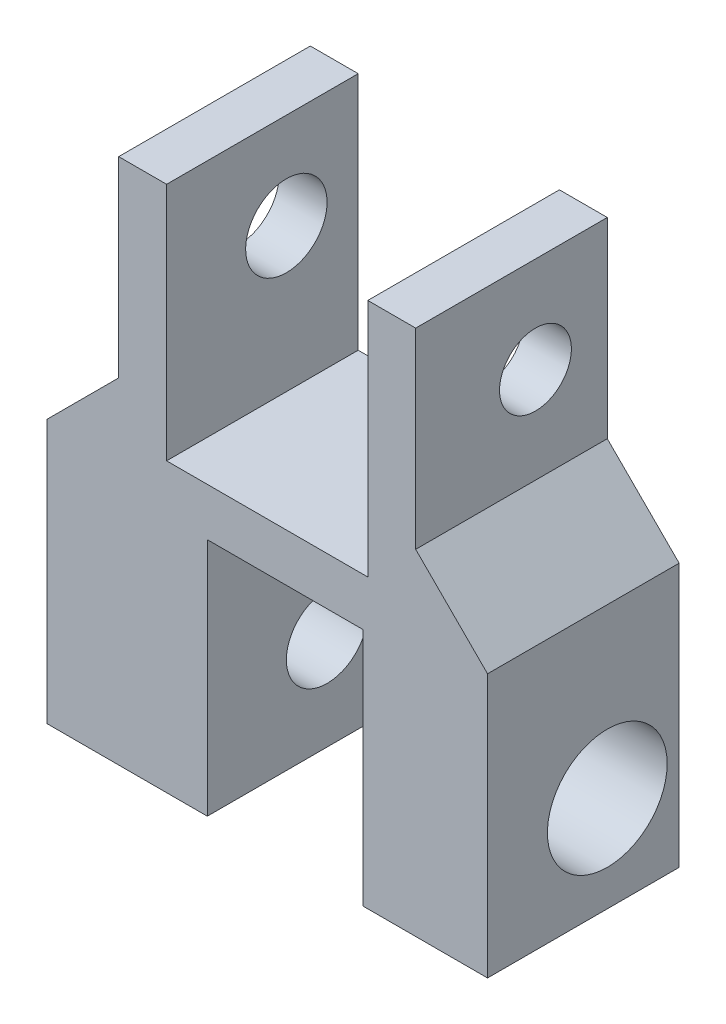
SolidWorks part; units mm, degrees
ref_plane "Ebene vorne" through (0, 0, 0) normal (0, 0, 1) x (1, 0, 0)
ref_plane "Ebene oben" through (0, 0, 0) normal (0, 1, 0) x (1, 0, 0)
ref_plane "Ebene rechts" through (0, 0, 0) normal (1, 0, 0) x (0, 0, -1)
sketch "Skizze2" plane through (0, 0, 0) normal (0, 0, 1) x (1, 0, 0)
  line L0 (-4.2, 0) -> (4.2, 0)
  line L1 (4.2, 0) -> (4.2, 10)
  line L2 (4.2, 10) -> (6.2, 10)
  line L3 (6.2, 10) -> (6.2, 2)
  line L4 (-6, -1) -> (-9.2, -1) construction
  line L5 (0, 0) -> (0, -14.4455) construction
  line L6 (-6.2, 10) -> (-6.2, 2)
  line L7 (-4.2, 10) -> (-6.2, 10)
  line L8 (-4.2, 0) -> (-4.2, 10)
  line L9 (-9.2, -1) -> (-9.2, -12)
  line L10 (-9.2, -12) -> (-2.5, -12)
  line L11 (9.2, -1) -> (9.2, -12)
  line L12 (6, -1) -> (9.2, -1) construction
  line L13 (-2.5, -12) -> (-2.5, -2)
  line L14 (-2.5, -2) -> (0, -2)
  line L15 (4, -12) -> (9.2, -12)
  line L16 (4, -12) -> (4, -2)
  line L17 (-9.2, -1) -> (-6.2, 2)
  line L18 (9.2, -1) -> (6.2, 2)
  line L19 (4, -2) -> (0, -2)
  dimension "D1" = 8.4
  dimension "D2" = 10
  dimension "D3" = 2
  dimension "D4" = 1
  dimension "D5" = 3
  dimension "D6" = 11
  dimension "D7" = 2.5
  dimension "D8" = 4
  dimension "D9" = 45
  dimension "D10" = 10
extrude "Aufsatz-Linear austragen1" add sketch "Skizze2" along normal blind 8
sketch "Skizze3" plane through (9.2, 0, 0) normal (-1, 0, 0) x (0, 0, 1)
  line L0 (4, -12) -> (4, -1) construction
  line L1 (8, -12) -> (0, -12) construction
  line L2 (8, -1) -> (0, -1) construction
  line L3 (0, -12) -> (0, -1) construction
  circle A0 centre (3, -8) radius 2.5
  dimension "D1" = 5
  dimension "D2" = 4
  dimension "D3" = 3
extrude "Schnitt-Linear austragen1" cut sketch "Skizze3" along normal blind 10
sketch "Skizze4" plane through (-9.2, 0, 0) normal (-1, 0, 0) x (0, 0, 1)
  circle A0 centre (3, -8) radius 1.7
  dimension "D1" = 3.4
extrude "Schnitt-Linear austragen2" cut sketch "Skizze4" against normal up to next
sketch "Skizze5" plane through (-6.2, 0, 0) normal (-1, 0, 0) x (0, 0, 1)
  line L0 (4, 10) -> (4, 2) construction
  line L1 (8, 10) -> (0, 10) construction
  line L2 (8, 2) -> (0, 2) construction
  line L3 (0, 0) -> (8, 0) construction
  line L4 (8, 2) -> (8, -1) construction
  line L5 (0, 10) -> (0, 2) construction
  circle A0 centre (3, 6) radius 1.7
  dimension "D1" = 6
  dimension "D2" = 3.4
  dimension "D3" = 3
extrude "Schnitt-Linear austragen3" cut sketch "Skizze5" against normal up to next
sketch "Skizze6" plane through (4.2, 0, 0) normal (-1, 0, 0) x (0, 0, 1)
  circle A0 centre (3, 6) radius 1.5
  dimension "D1" = 3
extrude "Schnitt-Linear austragen4" cut sketch "Skizze6" against normal blind 5
